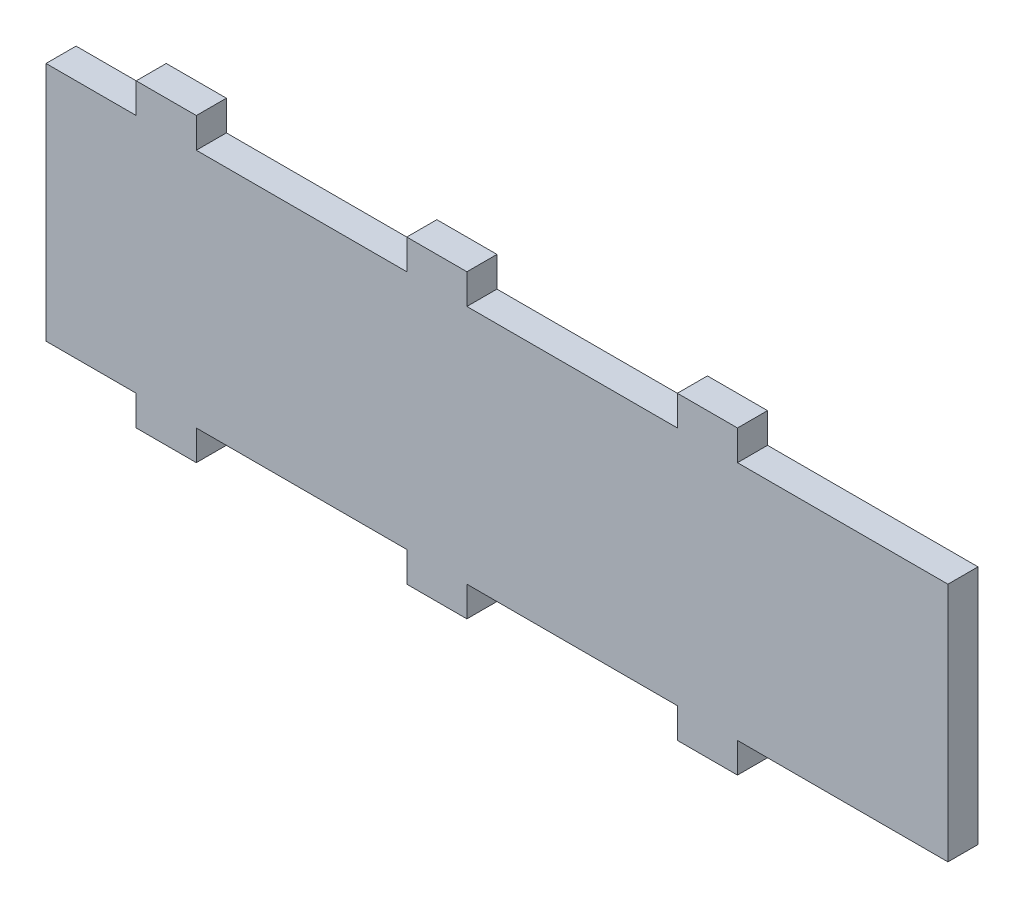
SolidWorks part; units mm, degrees
ref_plane "Plan de face" through (0, 0, 0) normal (0, 0, 1) x (1, 0, 0)
ref_plane "Plan de dessus" through (0, 0, 0) normal (0, 1, 0) x (1, 0, 0)
ref_plane "Plan de droite" through (0, 0, 0) normal (1, 0, 0) x (0, 0, -1)
sketch "Esquisse1" plane through (0, 0, 0) normal (0, 0, 1) x (1, 0, 0)
  line L0 (0, 20) -> (150, 20) construction
  line L1 (0, 0) -> (15, 0)
  line L2 (0, 0) -> (0, 40)
  line L3 (0, 40) -> (15, 40)
  line L4 (150, 0) -> (150, 40)
  line L5 (60, 0) -> (60, -5)
  line L6 (70, 0) -> (105, 0)
  line L7 (15, 0) -> (15, -5)
  line L8 (15, -5) -> (25, -5)
  line L9 (25, 0) -> (25, -5)
  line L10 (115, 0) -> (150, 0)
  line L11 (70, 0) -> (70, -5)
  line L12 (60, -5) -> (70, -5)
  line L13 (105, 0) -> (105, -5)
  line L14 (115, 40) -> (115, 45)
  line L15 (115, 0) -> (115, -5)
  line L16 (105, -5) -> (115, -5)
  line L17 (25, 0) -> (60, 0)
  line L18 (105, 45) -> (115, 45)
  line L19 (105, 40) -> (105, 45)
  line L20 (70, 40) -> (70, 45)
  line L21 (60, 45) -> (70, 45)
  line L22 (60, 40) -> (60, 45)
  line L23 (25, 40) -> (25, 45)
  line L24 (15, 45) -> (25, 45)
  line L25 (15, 40) -> (15, 45)
  line L26 (25, 40) -> (60, 40)
  line L27 (70, 40) -> (105, 40)
  line L28 (115, 40) -> (150, 40)
  dimension "D1" = 40
  dimension "D2" = 150
  dimension "D3" = 5
  dimension "D4" = 10
  dimension "D5" = 15
  dimension "D7" = 35
  dimension "D6" = 35
extrude "Boss.-Extru.1" add sketch "Esquisse1" along normal blind 5
